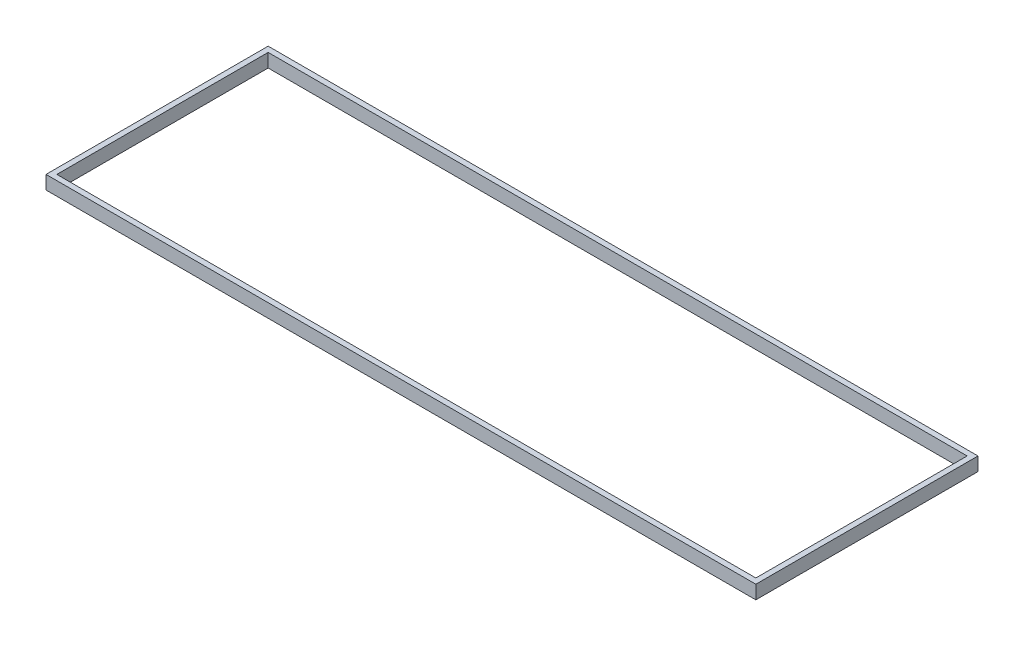
SolidWorks part; units mm, degrees
ref_plane "Front Plane" through (0, 0, 0) normal (0, 0, 1) x (1, 0, 0)
ref_plane "Top Plane" through (0, 0, 0) normal (0, 1, 0) x (1, 0, 0)
ref_plane "Right Plane" through (0, 0, 0) normal (1, 0, 0) x (0, 0, -1)
sketch "Sketch1" plane through (0, 0, 0) normal (0, 1, 0) x (1, 0, 0)
  line L1 (0, 0) -> (262, 0)
  line L2 (0, 0) -> (0, 82)
  line L3 (0, 82) -> (262, 82)
  line L4 (262, 0) -> (262, 82)
  line L5 (2, 2) -> (260, 2)
  line L6 (2, 2) -> (2, 80)
  line L7 (2, 80) -> (260, 80)
  line L8 (260, 2) -> (260, 80)
  line L9 (260, 80) -> (262, 80) construction
  line L10 (260, 80) -> (260, 82) construction
  line L11 (260, 82) -> (262, 82) construction
  line L12 (262, 80) -> (262, 82) construction
  line L13 (2, 2) -> (0, 2) construction
  line L14 (2, 2) -> (2, 0) construction
  line L15 (2, 0) -> (0, 0) construction
  line L16 (0, 2) -> (0, 0) construction
  circle A0 centre (251, 71) radius 9 construction
  point P9 (206.0467, 121.502)
  point P14 (275.3692, 89.8541)
  dimension "D1" = 2
extrude "Boss-Extrude1" add sketch "Sketch1" along normal blind 5
